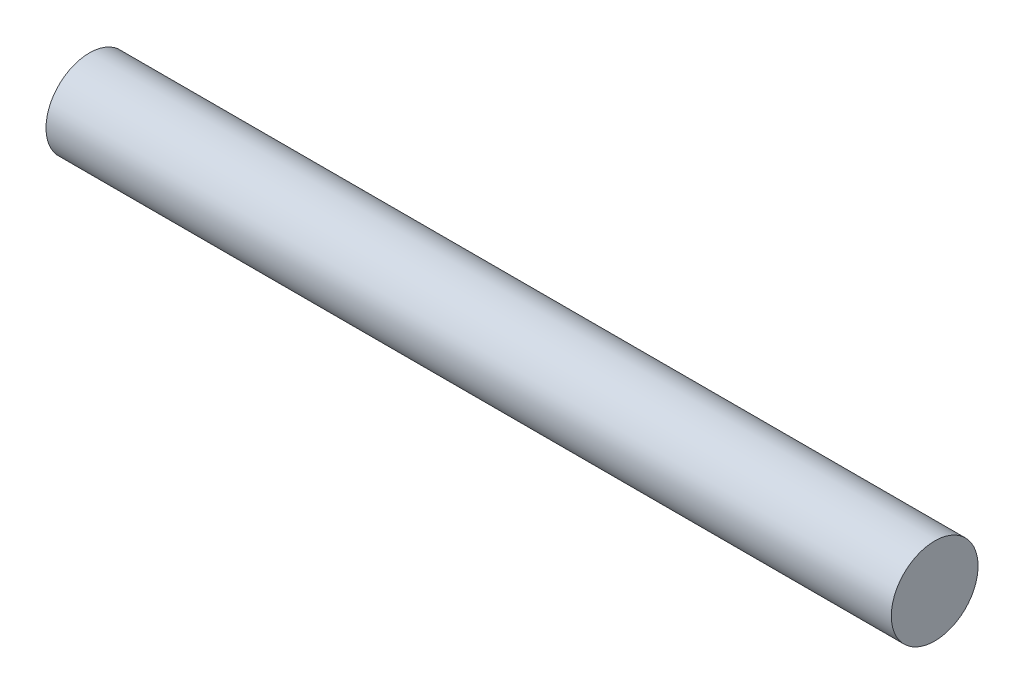
SolidWorks part; units mm, degrees
ref_plane "Front Plane" through (0, 0, 0) normal (0, 0, 1) x (1, 0, 0)
ref_plane "Top Plane" through (0, 0, 0) normal (0, 1, 0) x (1, 0, 0)
ref_plane "Right Plane" through (0, 0, 0) normal (1, 0, 0) x (0, 0, -1)
sketch "Sketch1" plane through (0, 0, 0) normal (1, 0, 0) x (0, 0, -1)
  circle A0 centre (0, 0) radius 3.57
  dimension "D1" = 7.14
extrude "Boss-Extrude2" add sketch "Sketch1" along normal up to surface (69.5469 mm away)
